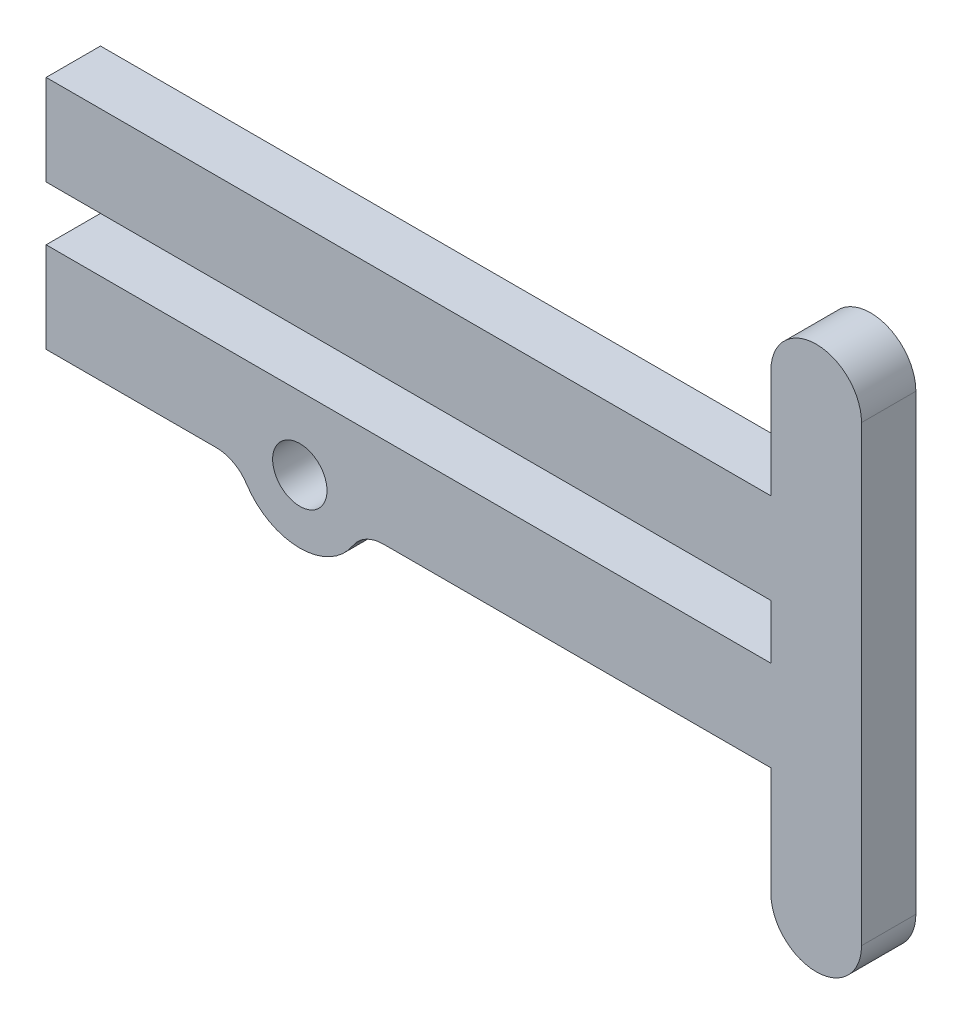
SolidWorks part; units mm, degrees
ref_plane "前视基准面" through (0, 0, 0) normal (0, 0, 1) x (1, 0, 0)
ref_plane "上视基准面" through (0, 0, 0) normal (0, 1, 0) x (1, 0, 0)
ref_plane "右视基准面" through (0, 0, 0) normal (1, 0, 0) x (0, 0, -1)
sketch "草图1" plane through (0, 0, 0) normal (0, 0, 1) x (1, 0, 0)
  line L8 (-45, 0) -> (0, 0)
  line L9 (0, 0) -> (0, -13)
  line L10 (0, -13) -> (-45, -13)
  line L11 (-45, -13) -> (-45, -8)
  line L12 (-45, -8) -> (-5, -8)
  line L13 (-5, -8) -> (-5, -5)
  line L14 (-5, -5) -> (-45, -5)
  line L15 (-45, -5) -> (-45, 0)
  line L16 (-5, -8) -> (-5, -13) construction
  dimension "D1" = 5
  dimension "D2" = 5
  dimension "D3" = 3
  dimension "D4" = 5
  dimension "D5" = 45
  dimension "D7" = 5
extrude "凸台-拉伸1" add sketch "草图1" along normal blind 3
sketch "草图2" plane through (0, 0, 3) normal (0, 0, 1) x (1, 0, 0)
  line L2 (0, -13) -> (0, 0) construction
  line L3 (-5, -8) -> (-45, -8) construction
  circle A0 centre (-31, -12) radius 3.5
  dimension "D1" = 7
  dimension "D2" = 31
  dimension "D3" = 4
extrude "凸台-拉伸2" add sketch "草图2" against normal up to surface (3 mm away) up to face at (-23.75, -6.5, 0)
sketch "草图3" plane through (0, 0, 3) normal (0, 0, 1) x (1, 0, 0)
  circle A0 centre (-31, -12) radius 1.5
  dimension "D1" = 3
extrude "切除-拉伸1" cut sketch "草图3" against normal through all
sketch "草图4" plane through (0, 0, 0) normal (0, 0, 1) x (1, 0, 0)
  line L0 (-2.5, 6) -> (-2.5, -19) construction
  line L1 (0, 6) -> (0, -19)
  line L2 (-5, 6) -> (-5, -19)
  line L3 (0, -13) -> (0, 0) construction
  line L4 (-5, -5) -> (-5, -8) construction
  line L5 (-6.1617, -6.5) -> (0.8171, -6.5) construction
  line L6 (0, 0) -> (-45, 0) construction
  line L7 (-27.6459, -13) -> (0, -13) construction
  arc A0 (0, 6) -> (-5, 6) centre (-2.5, 6) ccw
  arc A1 (-5, -19) -> (0, -19) centre (-2.5, -19) ccw
  point P2 (-2.5, -6.5)
  dimension "D1" = 25
extrude "凸台-拉伸3" add sketch "草图4" along normal up to surface (3 mm away) up to face at (-29.5, -12, 3)
fillet "圆角1" radius 2 2 edges at (-34.3541, -13, 1.5) (-27.6459, -13, 1.5)
